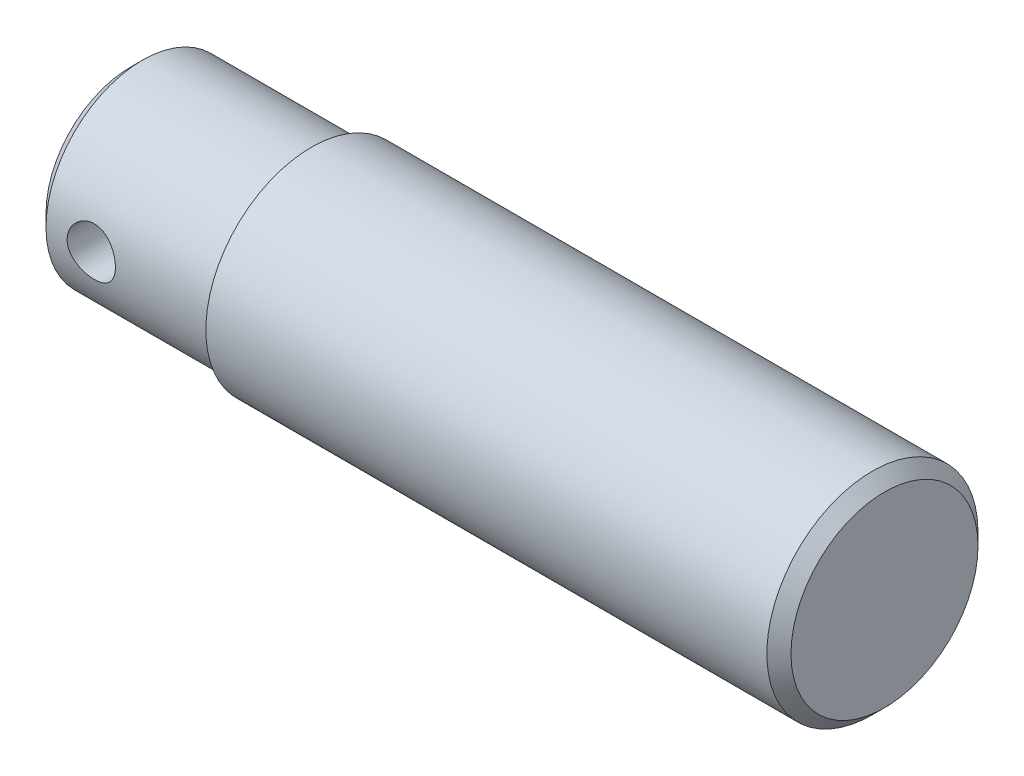
SolidWorks part; units mm, degrees
material "C40 or 38NiCrMo4"
ref_plane "Piano frontale" through (0, 0, 0) normal (0, 0, 1) x (1, 0, 0)
ref_plane "Piano superiore" through (0, 0, 0) normal (0, 1, 0) x (1, 0, 0)
ref_plane "Piano destro" through (0, 0, 0) normal (1, 0, 0) x (0, 0, -1)
sketch "Schizzo1" plane through (0, 0, 0) normal (1, 0, 0) x (0, 0, -1)
  circle A0 centre (0, 0) radius 17.5
extrude "Estrusione1" add sketch "Schizzo1" along normal blind 95
sketch "Schizzo2" plane through (0, 0, 0) normal (-1, 0, 0) x (0, 0, 1)
  circle A0 centre (0, 0) radius 16
extrude "Estrusione2" add sketch "Schizzo2" along normal blind 30
sketch "Schizzo3" plane through (-30, 0, 0) normal (-1, 0, 0) x (0, 0, 1)
  circle A0 centre (0, 0) radius 14
extrude "Estrusione3" [suppressed] add sketch "Schizzo3" along normal blind 2
sketch "Schizzo4" [suppressed] plane through (-20, 0, 0) normal (-1, 0, 0) x (0, 0, 1)
  circle A0 centre (0, 0) radius 16
extrude "Estrusione5" [suppressed] add sketch "Schizzo4" along normal blind 4
chamfer "Smusso1" [suppressed] distance 2 angle 45
chamfer "Smusso2" distance 2 angle 45 1 edges at (95, 0, -17.5)
chamfer "Smusso3" distance 2 angle 45 1 edges at (-30, 0, 16)
sketch "Schizzo5" plane through (0, 0, 0) normal (0, 0, 1) x (1, 0, 0)
  line L0 (0, 0) -> (-40.9506, 0) construction
  line L1 (-20.5, 26.8225) -> (-20.5, -25.238) construction
  line L2 (0, 17.5) -> (0, -17.5) construction
  circle A0 centre (-20.5, 0) radius 4
  dimension "D2" = 8
  dimension "D1" = 20.5
extrude "Estrusione6" cut sketch "Schizzo5" against normal through all and the other way through all
